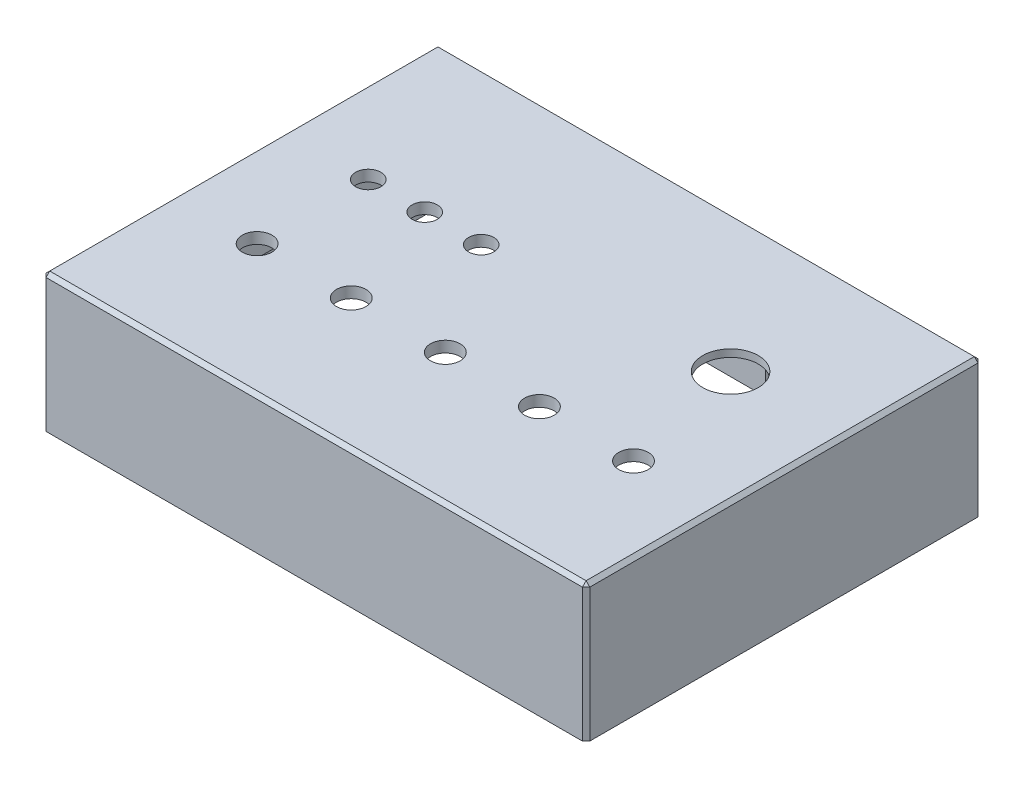
SolidWorks part; units mm, degrees
ref_plane "Спереди" through (0, 0, 0) normal (0, 0, 1) x (1, 0, 0)
ref_plane "Сверху" through (0, 0, 0) normal (0, 1, 0) x (1, 0, 0)
ref_plane "Справа" through (0, 0, 0) normal (1, 0, 0) x (0, 0, -1)
other "Configuration Table"
sketch "Эскиз1" plane through (0, 0, 0) normal (0, 1, 0) x (1, 0, 0)
  line L0 (-35.2, 25.2) -> (35.2, 25.2)
  line L1 (-35, -25) -> (35, -25) construction
  line L2 (-35, -25) -> (-35, 25) construction
  line L3 (-35, 25) -> (35, 25) construction
  line L4 (35, -25) -> (35, 25) construction
  line L5 (-35, -25) -> (35, 25) construction
  line L6 (-35, 25) -> (35, -25) construction
  line L7 (35.2, -25.2) -> (35.2, 25.2)
  line L8 (-35.2, -25.2) -> (35.2, -25.2)
  line L9 (-35.2, -25.2) -> (-35.2, 25.2)
  line L10 (-36.7, 26.7) -> (36.7, 26.7)
  line L11 (36.7, -26.7) -> (36.7, 26.7)
  line L12 (-36.7, -26.7) -> (36.7, -26.7)
  line L13 (-36.7, -26.7) -> (-36.7, 26.7)
  point P0 (0, 0)
  dimension "D1" = 70
  dimension "D2" = 50
  dimension "D3" = 0.2
  dimension "D4" = 1.5
extrude "Бобышка-Вытянуть1" add sketch "Эскиз1" against normal blind 17
sketch "Эскиз2" plane through (0, 0, 0) normal (0, 1, 0) x (1, 0, 0)
  line L1 (-36.7, 26.7) -> (36.7, 26.7)
  line L2 (-36.7, 26.7) -> (-36.7, -26.7)
  line L3 (-36.7, -26.7) -> (36.7, -26.7)
  line L4 (36.7, 26.7) -> (36.7, -26.7)
  line L5 (-36.7, 26.7) -> (36.7, -26.7) construction
  line L6 (-36.7, -26.7) -> (36.7, 26.7) construction
  point P4 (0, 0)
extrude "Бобышка-Вытянуть2" add sketch "Эскиз2" along normal blind 1.5
sketch "Эскиз3" plane through (0, 0, 0) normal (0, 1, 0) x (1, 0, 0)
  line L0 (-35.2, -25.2) -> (-35.2, 25.2) construction
  line L1 (-35.2, 25.2) -> (-30.7, 25.2)
  line L2 (-35.2, 25.2) -> (-35.2, 20.7)
  line L3 (-35.2, 20.7) -> (-30.7, 20.7)
  line L4 (-30.7, 25.2) -> (-30.7, 20.7)
  line L5 (-35.2, 25.2) -> (-30.7, 20.7) construction
  line L6 (-35.2, 20.7) -> (-30.7, 25.2) construction
  line L7 (-35.2, 25.2) -> (35.2, 25.2) construction
  line L8 (0, 0) -> (0, 17.8052) construction
  line L9 (0, 0) -> (16.7249, 0) construction
  line L10 (35.2, 20.7) -> (30.7, 25.2) construction
  line L11 (35.2, 25.2) -> (30.7, 20.7) construction
  line L12 (30.7, 25.2) -> (30.7, 20.7)
  line L13 (35.2, 20.7) -> (30.7, 20.7)
  line L14 (35.2, 25.2) -> (35.2, 20.7)
  line L15 (35.2, 25.2) -> (30.7, 25.2)
  line L16 (-35.2, -20.7) -> (-30.7, -25.2) construction
  line L17 (-35.2, -25.2) -> (-30.7, -20.7) construction
  line L18 (-30.7, -25.2) -> (-30.7, -20.7)
  line L19 (-35.2, -20.7) -> (-30.7, -20.7)
  line L20 (-35.2, -25.2) -> (-35.2, -20.7)
  line L21 (-35.2, -25.2) -> (-30.7, -25.2)
  line L22 (35.2, -25.2) -> (30.7, -20.7) construction
  line L23 (35.2, -20.7) -> (30.7, -25.2) construction
  line L24 (35.2, -25.2) -> (30.7, -25.2)
  line L25 (35.2, -25.2) -> (35.2, -20.7)
  line L26 (35.2, -20.7) -> (30.7, -20.7)
  line L27 (30.7, -25.2) -> (30.7, -20.7)
  point P4 (-32.95, 22.95)
  point P17 (32.95, 22.95)
  point P22 (-32.95, -22.95)
  point P27 (32.95, -22.95)
  dimension "D1" = 4.5
  dimension "D2" = 4.5
extrude "Бобышка-Вытянуть3" add sketch "Эскиз3" against normal blind 10.5
sketch "Эскиз4" plane through (0, 0, 0) normal (0, 1, 0) x (1, 0, 0)
  line L0 (-32.0016, -9) -> (2.1785, -9) construction
  line L1 (0, 0) -> (0, -5.8612) construction
  line L2 (-35, -25) -> (35, -25) construction
  line L3 (-30.1624, 6) -> (-4.7316, 6) construction
  line L4 (-25.4, 15.3008) -> (-25.4, 3.9486) construction
  line L5 (-25.4, -14.0669) -> (-25.4, -4.2571) construction
  line L7 (-35, 25) -> (35, 25) construction
  line L8 (26.8676, 8) -> (15.7005, 8) construction
  line L9 (21.5, 2.2211) -> (21.5, 12.7712) construction
  line L10 (35, -25) -> (35, 25) construction
  circle A0 centre (-25.4, -9) radius 2
  circle A1 centre (-12.7, -9) radius 2
  circle A2 centre (0, -9) radius 2
  circle A3 centre (12.7, -9) radius 2
  circle A4 centre (25.4, -9) radius 2
  circle A5 centre (-25.4, 6) radius 1.7
  circle A6 centre (-17.78, 6) radius 1.7
  circle A7 centre (-10.16, 6) radius 1.7
  circle A8 centre (21.5, 8) radius 3.75
  dimension "D1" = 5
  dimension "D3" = 3
  dimension "D5" = 13.5
  dimension "D2" = 16
  dimension "D4" = 19
  dimension "D6" = 17
extrude "Вырез-Вытянуть1" cut sketch "Эскиз4" along normal up to next
sketch "Эскиз5" plane through (0, -10.5, 0) normal (0, -1, 0) x (1, 0, 0)
  line L0 (-35, 25) -> (35, 25) construction
  line L1 (-35, 25) -> (-35, -25) construction
  line L2 (0, 0) -> (0, -10.588) construction
  line L3 (0, 0) -> (10.9295, 0) construction
  circle A0 centre (-33, 23) radius 1
  circle A1 centre (33, 23) radius 1
  circle A2 centre (33, -23) radius 1
  circle A3 centre (-33, -23) radius 1
  dimension "D1" = 2
  dimension "D2" = 2
extrude "Вырез-Вытянуть2" cut sketch "Эскиз5" against normal blind 7
sketch "Эскиз6" plane through (0, -17, 0) normal (0, -1, 0) x (1, 0, 0)
  line L0 (36.7, 26.7) -> (36.7, -26.7) construction
  line L1 (-35.9, -25.9) -> (35.9, -25.9)
  line L2 (-35.9, -25.9) -> (-35.9, 25.9)
  line L3 (-35.9, 25.9) -> (35.9, 25.9)
  line L4 (35.9, -25.9) -> (35.9, 25.9)
  line L5 (-35.9, -25.9) -> (35.9, 25.9) construction
  line L6 (-35.9, 25.9) -> (35.9, -25.9) construction
  line L7 (-36.7, 26.7) -> (36.7, 26.7) construction
  point P0 (0, 0)
  dimension "D1" = 0.8
  dimension "D2" = 0.8
extrude "Вырез-Вытянуть3" cut sketch "Эскиз6" against normal blind 7
chamfer "Фаска1" distance 0.5 angle 45 8 edges at (0, 1.5, 26.7) (-36.7, -7.75, 26.7) (-36.7, 1.5, 0) (-36.7, -7.75, -26.7) (0, 1.5, -26.7) (36.7, -7.75, -26.7) (36.7, 1.5, 0) (36.7, -7.75, 26.7)
sketch "Эскиз7" plane through (0, 0, -26.7) normal (0, 0, -1) x (-1, 0, 0)
  line L0 (-36.2, -17) -> (36.2, -17) construction
  line L1 (-8.3, -13.8) -> (-8.3, -17)
  line L2 (-8.3, -17) -> (-14.7, -17)
  line L3 (-14.7, -17) -> (-14.7, -13.8)
  line L4 (22.2, -13.8) -> (22.2, -17)
  line L5 (22.2, -17) -> (15.8, -17)
  line L6 (15.8, -17) -> (15.8, -13.8)
  arc A0 (-8.3, -13.8) -> (-14.7, -13.8) centre (-11.5, -13.8) ccw
  arc A1 (22.2, -13.8) -> (15.8, -13.8) centre (19, -13.8) ccw
  dimension "D1" = 3.2
  dimension "D3" = 16
  dimension "D2" = 2
extrude "Вырез-Вытянуть4" cut sketch "Эскиз7" against normal up to next
sketch "Эскиз8" plane through (0, 1.5, 0) normal (0, 1, 0) x (1, 0, 0)
  line L0 (-29.4602, -15) -> (29.09, -15) construction
  circle A0 centre (-25.4, -9) radius 2 construction
  text T0 "KEY"
  dimension "D1" = 6
sketch "Эскиз9" plane through (0, 0, 0) normal (0, 1, 0) x (1, 0, 0)
  line L1 (16, 1.5) -> (27, 1.5)
  line L2 (16, 1.5) -> (16, 14.5)
  line L3 (16, 14.5) -> (27, 14.5)
  line L4 (27, 1.5) -> (27, 14.5)
  line L5 (16, 1.5) -> (27, 14.5) construction
  line L6 (16, 14.5) -> (27, 1.5) construction
  point P0 (21.5, 8)
  dimension "D1" = 11
  dimension "D2" = 13
extrude "Вырез-Вытянуть5" cut sketch "Эскиз9" along normal blind 0.5
